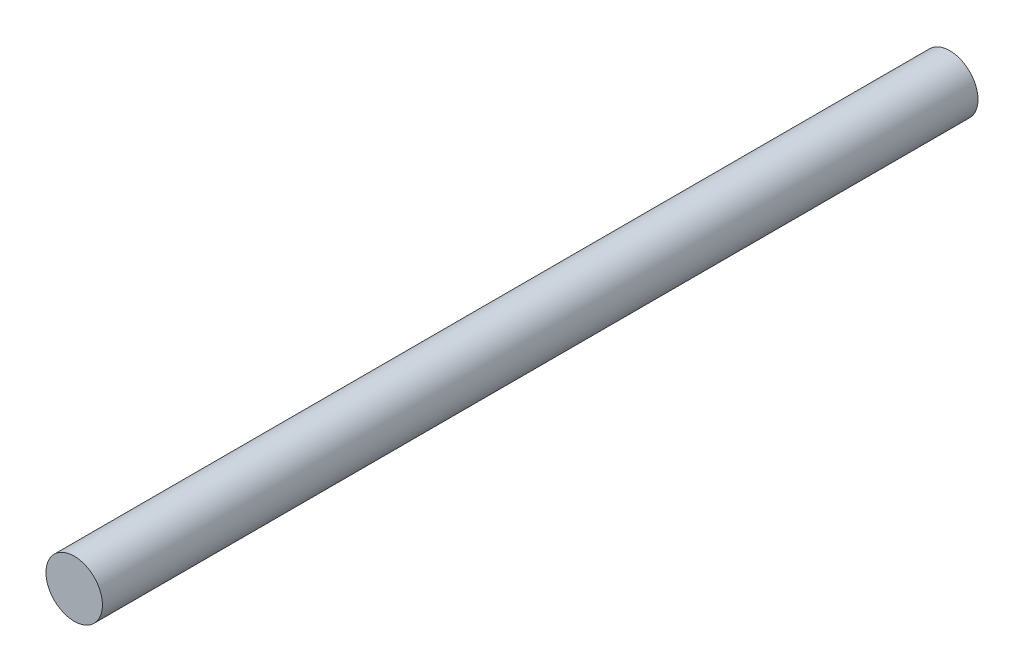
SolidWorks part; units mm, degrees
ref_plane "Front Plane" through (0, 0, 0) normal (0, 0, 1) x (1, 0, 0)
ref_plane "Top Plane" through (0, 0, 0) normal (0, 1, 0) x (1, 0, 0)
ref_plane "Right Plane" through (0, 0, 0) normal (1, 0, 0) x (0, 0, -1)
sketch "Sketch1" plane through (0, 0, 0) normal (0, 0, 1) x (1, 0, 0)
  circle A0 centre (0, 0) radius 4
  dimension "D1" = 8
extrude "Boss-Extrude1" add sketch "Sketch1" along normal blind 124
